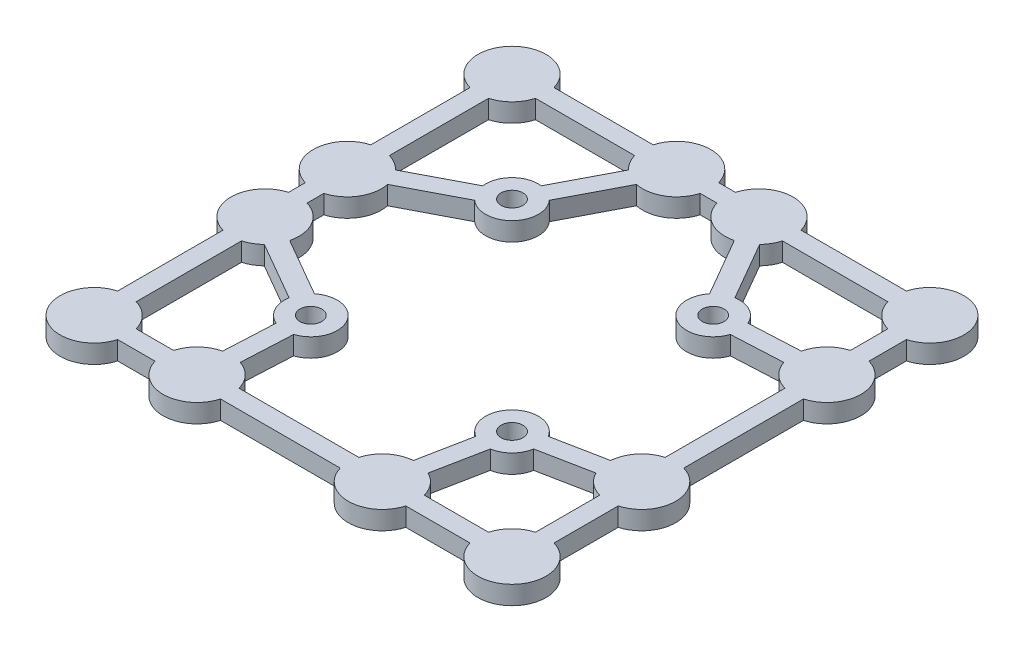
SolidWorks part; units mm, degrees
ref_plane "Front Plane" through (0, 0, 0) normal (0, 0, 1) x (1, 0, 0)
ref_plane "Top Plane" through (0, 0, 0) normal (0, 1, 0) x (1, 0, 0)
ref_plane "Right Plane" through (0, 0, 0) normal (1, 0, 0) x (0, 0, -1)
sketch "Sketch1" plane through (0, 0, 0) normal (0, 1, 0) x (1, 0, 0)
  line L0 (-56.5, -56.5) -> (-56.5, 56.5) construction
  line L1 (-32.5, -32.5) -> (32.5, -32.5) construction
  line L2 (-32.5, -32.5) -> (-32.5, 32.5) construction
  line L3 (-32.5, 32.5) -> (32.5, 32.5) construction
  line L4 (32.5, -32.5) -> (32.5, 32.5) construction
  line L5 (-32.5, -32.5) -> (32.5, 32.5) construction
  line L6 (-32.5, 32.5) -> (32.5, -32.5) construction
  line L7 (-56.5, 56.5) -> (56.5, 56.5) construction
  line L8 (56.5, -56.5) -> (56.5, 56.5) construction
  line L9 (-56.5, -56.5) -> (56.5, -56.5) construction
  line L10 (-78.5, -78.5) -> (-78.5, 78.5) construction
  line L11 (-78.5, 78.5) -> (78.5, 78.5) construction
  line L12 (78.5, -78.5) -> (78.5, 78.5) construction
  line L13 (-78.5, -78.5) -> (78.5, -78.5) construction
  line L14 (-67.5, -67.5) -> (-67.5, 67.5) construction
  line L15 (-67.5, 67.5) -> (67.5, 67.5) construction
  line L16 (67.5, -67.5) -> (67.5, 67.5) construction
  line L17 (-67.5, -67.5) -> (67.5, -67.5) construction
  line L18 (-56.917, 70.5) -> (-24.883, 70.5)
  line L19 (36.183, -64.5) -> (56.917, -64.5)
  line L20 (-56.917, -70.5) -> (-44.833, -70.5)
  line L21 (-70.5, -56.917) -> (-70.5, -22.883)
  line L22 (-56.917, 64.5) -> (-24.883, 64.5)
  line L23 (-64.5, -64.5) -> (64.5, -64.5) construction
  line L24 (-70.5, -1.717) -> (-70.5, 3.717)
  line L25 (-64.5, -56.917) -> (-64.5, -22.883)
  line L26 (-70.5, 70.5) -> (70.5, 70.5) construction
  line L27 (-70.5, -70.5) -> (-70.5, 70.5) construction
  line L28 (-64.5, 64.5) -> (64.5, 64.5) construction
  line L29 (-64.5, -64.5) -> (-64.5, 64.5) construction
  line L30 (-3.717, 70.5) -> (1.717, 70.5)
  line L31 (-3.717, 64.5) -> (1.717, 64.5)
  line L32 (22.883, 70.5) -> (56.917, 70.5)
  line L33 (22.883, 64.5) -> (56.917, 64.5)
  line L34 (70.5, -70.5) -> (70.5, 70.5) construction
  line L35 (64.5, -64.5) -> (64.5, 64.5) construction
  line L36 (64.5, 44.833) -> (64.5, 56.917)
  line L37 (70.5, 44.833) -> (70.5, 56.917)
  line L38 (64.5, -15.017) -> (64.5, 23.667)
  line L39 (70.5, -15.017) -> (70.5, 23.667)
  line L40 (64.5, -56.917) -> (64.5, -36.183)
  line L41 (70.5, -56.917) -> (70.5, -36.183)
  line L42 (-70.5, -70.5) -> (70.5, -70.5) construction
  line L43 (36.183, -70.5) -> (56.917, -70.5)
  line L44 (-23.667, -64.5) -> (15.017, -64.5)
  line L45 (-23.667, -70.5) -> (15.017, -70.5)
  line L46 (-56.917, -64.5) -> (-44.833, -64.5)
  line L47 (-64.5, -1.717) -> (-64.5, 3.717)
  line L48 (-64.5, 24.883) -> (-64.5, 56.917)
  line L49 (-70.5, 24.883) -> (-70.5, 56.917)
  line L50 (-18.4522, 59.515) -> (-30.8737, 35.6274) construction
  line L51 (-35.6274, 30.8737) -> (-59.515, 18.4522) construction
  line L52 (16.7988, 59.7051) -> (30.738, 35.553) construction
  line L53 (36.0206, 32.676) -> (58.5112, 33.8006) construction
  line L54 (58.67, -27.3408) -> (35.9584, -31.8182) construction
  line L55 (31.8182, -35.9584) -> (27.3408, -58.67) construction
  line L56 (-33.8006, -58.5112) -> (-32.676, -36.0206) construction
  line L57 (-59.7051, -16.7988) -> (-35.553, -30.738) construction
  line L58 (-21.8441, 59.4946) -> (-31.4802, 40.9638)
  line L59 (-16.5208, 56.7265) -> (-26.1569, 38.1957)
  line L60 (-40.9638, 31.4802) -> (-59.4946, 21.8441)
  line L61 (-38.1957, 26.1569) -> (-56.7265, 16.5208)
  line L62 (14.9918, 56.8344) -> (25.9129, 37.9116)
  line L63 (-37.0115, 33.5354) -> (-60.8991, 21.1138) construction
  line L64 (-34.2434, 28.2121) -> (-58.131, 15.7905) construction
  line L65 (-15.7905, 58.131) -> (-28.2121, 34.2434) construction
  line L66 (-21.1138, 60.8991) -> (-33.5354, 37.0115) construction
  line L67 (40.6196, 29.9022) -> (57.08, 30.7253)
  line L68 (20.1884, 59.8336) -> (31.1095, 40.9108)
  line L69 (40.3199, 35.8947) -> (56.7804, 36.7178)
  line L70 (56.5366, -24.7036) -> (39.7488, -28.0132)
  line L71 (19.3971, 61.2047) -> (33.3363, 37.0526) construction
  line L72 (14.2005, 58.2055) -> (28.1397, 34.0534) construction
  line L73 (35.8708, 35.6723) -> (58.3614, 36.7968) construction
  line L74 (36.1704, 29.6798) -> (58.661, 30.8043) construction
  line L75 (28.0132, -39.7488) -> (24.7036, -56.5366)
  line L76 (57.6971, -30.5903) -> (40.9093, -33.8999)
  line L77 (33.8999, -40.9093) -> (30.5903, -57.6971)
  line L78 (-30.7253, -57.08) -> (-29.9022, -40.6196)
  line L79 (58.0897, -24.3974) -> (35.3782, -28.8748) construction
  line L80 (59.2502, -30.2841) -> (36.5387, -34.7615) construction
  line L81 (34.7615, -36.5387) -> (30.2841, -59.2502) construction
  line L82 (28.8748, -35.3782) -> (24.3974, -58.0897) construction
  line L83 (-59.8336, -20.1884) -> (-40.9108, -31.1095)
  line L84 (-36.7178, -56.7804) -> (-35.8947, -40.3199)
  line L85 (-56.8344, -14.9918) -> (-37.9116, -25.9129)
  line L87 (-61.2047, -19.3971) -> (-37.0526, -33.3363) construction
  line L88 (-58.2055, -14.2005) -> (-34.0534, -28.1397) construction
  line L89 (-36.7968, -58.3614) -> (-35.6723, -35.8708) construction
  line L90 (-30.8043, -58.661) -> (-29.6798, -36.1704) construction
  circle A0 centre (-32.5, 32.5) radius 22.5 construction
  circle A1 centre (32.5, 32.5) radius 22.5 construction
  circle A2 centre (32.5, -32.5) radius 22.5 construction
  circle A3 centre (-32.5, -32.5) radius 22.5 construction
  circle A4 centre (-67.5, 67.5) radius 9 construction
  circle A5 centre (-67.5, -67.5) radius 9 construction
  circle A6 centre (67.5, -67.5) radius 9 construction
  circle A7 centre (67.5, 67.5) radius 9 construction
  circle A8 centre (-67.5, -12.3) radius 9 construction
  circle A9 centre (-67.5, 14.3) radius 9 construction
  circle A10 centre (12.3, 67.5) radius 9 construction
  circle A11 centre (-14.3, 67.5) radius 9 construction
  circle A12 centre (-34.25, -67.5) radius 9 construction
  circle A13 centre (25.6, -67.5) radius 9 construction
  circle A14 centre (67.5, -25.6) radius 9 construction
  circle A15 centre (67.5, 34.25) radius 9 construction
  arc A16 (-56.917, 70.5) -> (-70.5, 56.917) centre (-67.5, 67.5) ccw
  arc A17 (-64.5, 3.717) -> (-56.7265, 16.5208) centre (-67.5, 14.3) ccw
  arc A18 (-64.5, -22.883) -> (-59.8336, -20.1884) centre (-67.5, -12.3) ccw
  arc A19 (-56.917, -64.5) -> (-64.5, -56.917) centre (-67.5, -67.5) ccw
  arc A20 (-23.667, -64.5) -> (-30.7253, -57.08) centre (-34.25, -67.5) ccw
  arc A21 (36.183, -64.5) -> (30.5903, -57.6971) centre (25.6, -67.5) ccw
  arc A22 (64.5, -56.917) -> (56.917, -64.5) centre (67.5, -67.5) ccw
  arc A23 (64.5, -15.017) -> (56.5366, -24.7036) centre (67.5, -25.6) ccw
  arc A24 (64.5, 44.833) -> (56.7804, 36.7178) centre (67.5, 34.25) ccw
  arc A25 (56.917, 64.5) -> (64.5, 56.917) centre (67.5, 67.5) ccw
  arc A26 (1.717, 64.5) -> (14.9918, 56.8344) centre (12.3, 67.5) ccw
  arc A27 (-24.883, 64.5) -> (-21.8441, 59.4946) centre (-14.3, 67.5) ccw
  arc A28 (-64.5, 56.917) -> (-56.917, 64.5) centre (-67.5, 67.5) ccw
  arc A29 (-3.717, 70.5) -> (-24.883, 70.5) centre (-14.3, 67.5) ccw
  arc A30 (22.883, 70.5) -> (1.717, 70.5) centre (12.3, 67.5) ccw
  arc A31 (70.5, 56.917) -> (56.917, 70.5) centre (67.5, 67.5) ccw
  arc A32 (70.5, 23.667) -> (70.5, 44.833) centre (67.5, 34.25) ccw
  arc A33 (70.5, -36.183) -> (70.5, -15.017) centre (67.5, -25.6) ccw
  arc A34 (56.917, -70.5) -> (70.5, -56.917) centre (67.5, -67.5) ccw
  arc A35 (15.017, -70.5) -> (36.183, -70.5) centre (25.6, -67.5) ccw
  arc A36 (-44.833, -70.5) -> (-23.667, -70.5) centre (-34.25, -67.5) ccw
  arc A37 (-70.5, -56.917) -> (-56.917, -70.5) centre (-67.5, -67.5) ccw
  arc A38 (-70.5, -1.717) -> (-70.5, -22.883) centre (-67.5, -12.3) ccw
  arc A39 (-70.5, 24.883) -> (-70.5, 3.717) centre (-67.5, 14.3) ccw
  circle A40 centre (-32.5, 32.5) radius 3.525
  arc A41 (-38.1957, 26.1569) -> (-26.1569, 38.1957) centre (-32.5, 32.5) ccw
  circle A42 centre (32.5, 32.5) radius 3.525
  circle A43 centre (32.5, -32.5) radius 3.525
  circle A44 centre (-32.5, -32.5) radius 3.525
  arc A45 (25.9129, 37.9116) -> (40.6196, 29.9022) centre (32.5, 32.5) ccw
  arc A46 (39.7488, -28.0132) -> (28.0132, -39.7488) centre (32.5, -32.5) ccw
  arc A47 (-40.9108, -31.1095) -> (-35.8947, -40.3199) centre (-32.5, -32.5) ccw
  arc A48 (-59.4946, 21.8441) -> (-64.5, 24.883) centre (-67.5, 14.3) ccw
  arc A49 (-31.4802, 40.9638) -> (-40.9638, 31.4802) centre (-32.5, 32.5) ccw
  circle A50 centre (-32.5, 32.5) radius 8.525 construction
  arc A51 (-16.5208, 56.7265) -> (-3.717, 64.5) centre (-14.3, 67.5) ccw
  arc A52 (20.1884, 59.8336) -> (22.883, 64.5) centre (12.3, 67.5) ccw
  arc A53 (40.3199, 35.8947) -> (31.1095, 40.9108) centre (32.5, 32.5) ccw
  circle A54 centre (32.5, 32.5) radius 8.525 construction
  arc A55 (57.6971, -30.5903) -> (64.5, -36.183) centre (67.5, -25.6) ccw
  arc A56 (57.08, 30.7253) -> (64.5, 23.667) centre (67.5, 34.25) ccw
  circle A57 centre (32.5, -32.5) radius 8.525 construction
  arc A58 (33.8999, -40.9093) -> (40.9093, -33.8999) centre (32.5, -32.5) ccw
  arc A59 (24.7036, -56.5366) -> (15.017, -64.5) centre (25.6, -67.5) ccw
  arc A60 (-56.8344, -14.9918) -> (-64.5, -1.717) centre (-67.5, -12.3) ccw
  arc A61 (-29.9022, -40.6196) -> (-37.9116, -25.9129) centre (-32.5, -32.5) ccw
  circle A62 centre (-32.5, -32.5) radius 8.525 construction
  arc A63 (-36.7178, -56.7804) -> (-44.833, -64.5) centre (-34.25, -67.5) ccw
  point P0 (0, 0)
  point P122 (-24.3475, 34.9925)
  point P142 (41.025, 32.5)
  point P163 (41.025, -32.5)
  point P186 (-23.975, -32.5)
  dimension "D3" = 24
  dimension "D7" = 135
  dimension "D15" = 5
  dimension "D16" = 5
  dimension "D1" = 65
  dimension "D2" = 65
  dimension "D4" = 113
  dimension "D8" = 79.8
  dimension "D9" = 53.2
  dimension "D10" = 33.25
  dimension "D11" = 135
  dimension "D12" = 93.1
  dimension "D5" = 22
  dimension "D6" = 11
  dimension "D13" = 3
  dimension "D14" = 3
  dimension "D17" = 5
  dimension "D18" = 5
  dimension "D19" = 3
  dimension "D20" = 3
  dimension "D21" = 3
  dimension "D22" = 3
  dimension "D23" = 3
  dimension "D24" = 3
  dimension "D25" = 3
  dimension "D26" = 3
  dimension "D27" = 3
  dimension "D28" = 3
extrude "Boss-Extrude1" add sketch "Sketch1" along normal blind 6
